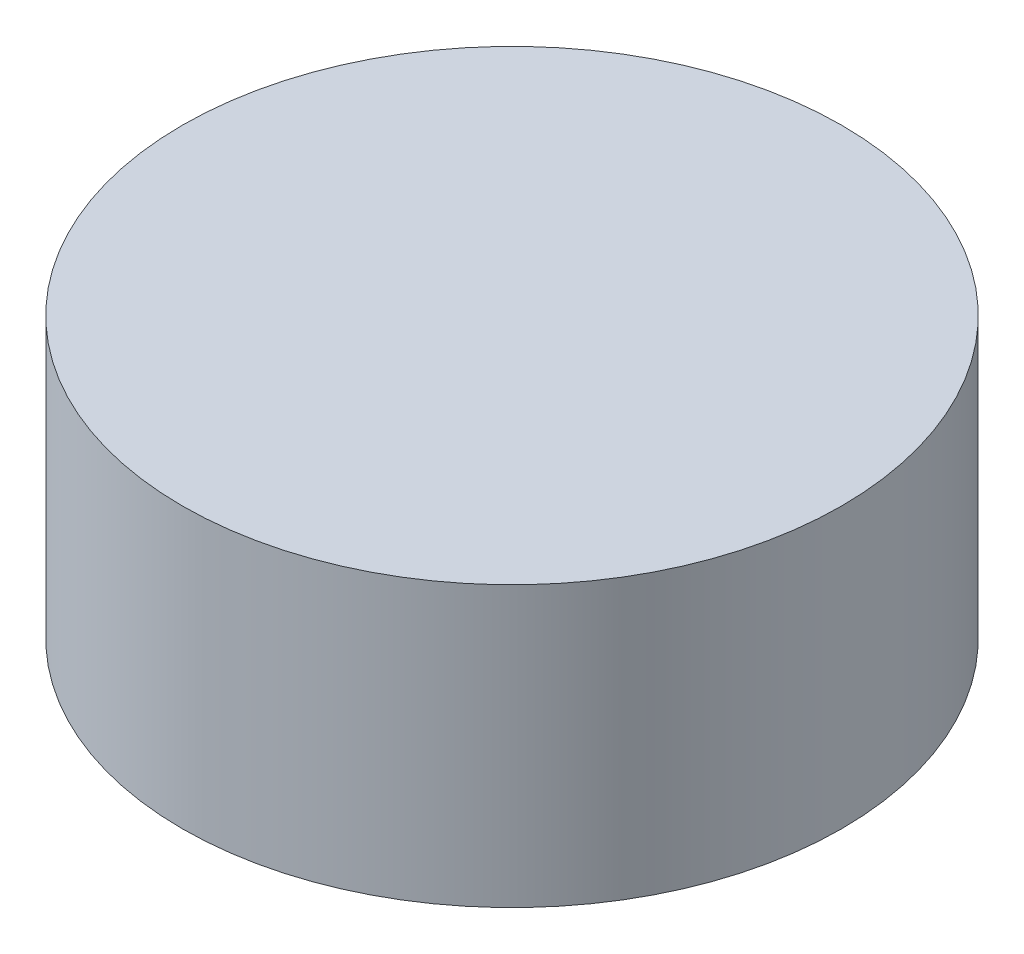
SolidWorks part; units mm, degrees
ref_plane "Front Plane" through (0, 0, 0) normal (0, 0, 1) x (1, 0, 0)
ref_plane "Top Plane" through (0, 0, 0) normal (0, 1, 0) x (1, 0, 0)
ref_plane "Right Plane" through (0, 0, 0) normal (1, 0, 0) x (0, 0, -1)
sketch "Sketch1" plane through (0, 0, 0) normal (1, 0, 0) x (0, 0, -1)
  line L0 (0, 225) -> (0, -185) construction
  line L1 (-30, -190) -> (-220, -190)
  line L8 (0, 0) -> (-562.5, 0) construction
  line L11 (-562.5, 225) -> (-562.5, -225)
  line L12 (-562.5, -225) -> (0, -225)
  line L13 (0, -225) -> (0, -185)
  line L14 (-275, -190) -> (-275, -215)
  line L15 (-275, -215) -> (-220, -215)
  line L16 (-220, -215) -> (-220, -190)
  line L17 (-275, -190) -> (-537.5, -190)
  line L19 (-562.5, 0) -> (-687.3372, 0) construction
  line L21 (-537.5, 185) -> (-537.5, -190)
  line L22 (-30, -190) -> (-30, 185)
  line L24 (0, -185) -> (0, 225)
  line L27 (-537.5, 185) -> (-537.5, 225)
  line L28 (-30, 225) -> (-30, 185)
  line L29 (-537.5, 225) -> (-30, 225)
  line L30 (-562.5, 225) -> (-562.5, 252.019)
  line L31 (-562.5, 252.019) -> (0, 252.019)
  line L32 (0, 252.019) -> (0, 225)
  dimension "D2" = 1075
  dimension "D3" = 450
  dimension "D4" = 225
  dimension "D5" = 1125
  dimension "D6" = 40
  dimension "D7" = 30
  dimension "D9" = 440
  dimension "D10" = 550
  dimension "D11" = 25
revolve "Revolve1" add sketch "Sketch1" angle 360 about L0
